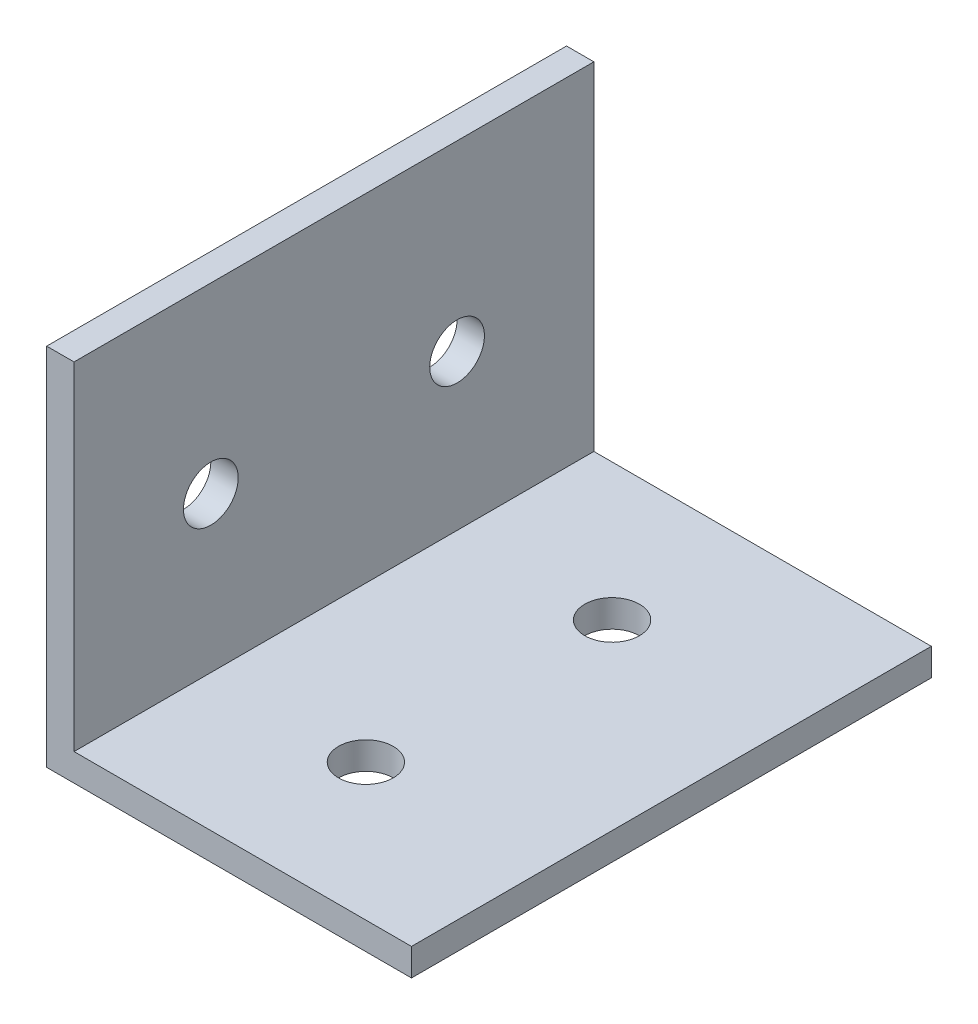
SolidWorks part; units mm, degrees
ref_plane "Plan de face" through (0, 0, 0) normal (0, 0, 1) x (1, 0, 0)
ref_plane "Plan de dessus" through (0, 0, 0) normal (0, 1, 0) x (1, 0, 0)
ref_plane "Plan de droite" through (0, 0, 0) normal (1, 0, 0) x (0, 0, -1)
sketch "Esquisse1" plane through (0, 0, 0) normal (0, 0, 1) x (1, 0, 0)
  line L0 (-16.9772, 3.8643) -> (-16.9772, -16.1357)
  line L1 (-16.9772, -16.1357) -> (3.0228, -16.1357)
  line L2 (3.0228, -16.1357) -> (3.0228, -14.6357)
  line L3 (3.0228, -14.6357) -> (-15.4772, -14.6357)
  line L4 (-15.4772, -14.6357) -> (-15.4772, 3.8643)
  line L5 (-15.4772, 3.8643) -> (-16.9772, 3.8643)
  dimension "D1" = 1.5
  dimension "D2" = 1.5
  dimension "D3" = 20
  dimension "D4" = 20
extrude "Extrusion1" add sketch "Esquisse1" along normal blind 28.5
sketch "Esquisse2" plane through (-16.9772, 0, 0) normal (-1, 0, 0) x (0, 0, 1)
  line L0 (21, -6.1357) -> (7.5, -6.1357) construction
  line L1 (28.5, 3.8643) -> (28.5, -16.1357) construction
  line L2 (28.5, 3.8643) -> (0, 3.8643) construction
  line L4 (0, -14.6357) -> (0, 3.8643) construction
  circle A0 centre (21, -6.1357) radius 1.5
  circle A1 centre (7.5, -6.1357) radius 1.5
  dimension "D1" = 7.5
  dimension "D2" = 7.5
  dimension "D3" = 10
extrude "Extrusion2" cut sketch "Esquisse2" against normal blind 47.5
sketch "Esquisse3" plane through (0, -16.1357, 0) normal (0, -1, 0) x (1, 0, 0)
  line L0 (-16.9772, 0) -> (3.0228, 0) construction
  line L1 (3.0228, 28.5) -> (3.0228, 0) construction
  line L2 (-16.9772, 28.5) -> (3.0228, 28.5) construction
  circle A0 centre (-6.9772, 7.5) radius 1.5
  circle A1 centre (-6.9772, 21) radius 1.5
  point P4 (-6.9772, 0)
  dimension "D1" = 7.5
  dimension "D2" = 10
  dimension "D3" = 10
  dimension "D4" = 7.5
extrude "Extrusion3" cut sketch "Esquisse3" against normal blind 10
